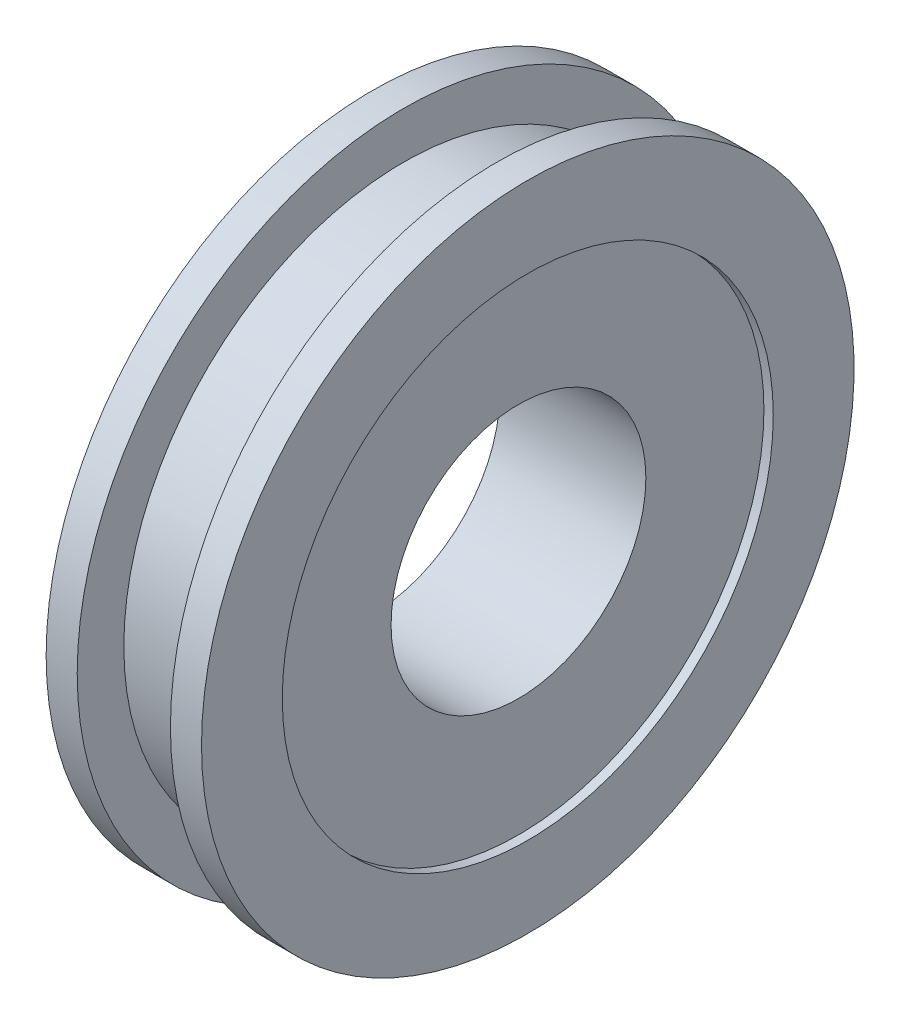
SolidWorks part; units mm, degrees
ref_plane "Front Plane" through (0, 0, 0) normal (0, 0, 1) x (1, 0, 0)
ref_plane "Top Plane" through (0, 0, 0) normal (0, 1, 0) x (1, 0, 0)
ref_plane "Right Plane" through (0, 0, 0) normal (1, 0, 0) x (0, 0, -1)
sketch "Sketch1" plane through (0, 0, 0) normal (0, 0, 1) x (1, 0, 0)
  line L0 (0, 0) -> (5.1881, 0) construction
  line L2 (-5.5, -0.875) -> (-5.5, 10.5) construction
  line L3 (-5.5, 10.5) -> (-0.5, 10.5)
  line L4 (-0.5, 4.1) -> (-0.5, 10.5)
  line L5 (-5.5, 10.5) -> (-5.5, 4.1)
  line L8 (-5.5, 4.1) -> (-0.5, 4.1)
  dimension "D1" = 10.5
  dimension "D2" = 5
  dimension "D5" = 4.1
revolve "Revolve1" add sketch "Sketch1" angle 360 about L0
sketch "Sketch2" plane through (0, 0, 0) normal (0, 0, 1) x (1, 0, 0)
  line L6 (0, 0) -> (5.4705, 0) construction
  line L9 (-0.5, 3.3693) -> (-0.5, 10.5) construction
  line L10 (-0.5, 10.5) -> (-1.5, 10.5) construction
  line L11 (-1.5, 10.5) -> (-1.5, 9) construction
  line L12 (-1.5, 9) -> (-5.5, 9) construction
  line L13 (-5.5, 9) -> (-5.5, 3.3693) construction
  line L14 (-0.5, 10.5) -> (-5.5, 10.5) construction
  line L15 (-0.5, -10.5) -> (-0.5, 10.5) construction
  line L16 (-5.5, 10.5) -> (-5.5, -10.5) construction
  line L17 (-1.5, 9) -> (-1.5, 10.5)
  line L18 (-1.5, 10.5) -> (-4.5, 10.5)
  line L20 (-4.5, 10.5) -> (-4.5, 9)
  line L21 (-4.5, 9) -> (-1.5, 9)
  line L22 (-4.5, 10.5) -> (-5.5, 10.5) construction
  line L23 (-1.5, 10.5) -> (-0.5, 10.5) construction
  dimension "D1" = 9
  dimension "D2" = 3
  dimension "D3" = 1
  dimension "D5" = 1.5
revolve "Cut-Revolve1" cut sketch "Sketch2" angle 360 about L6
sketch "Sketch3" plane through (0, 0, 0) normal (1, 0, 0) x (0, 0, -1)
  circle A0 centre (0, 0) radius 7.9
  dimension "D1" = 15.8
extrude "Cut-Extrude1" cut sketch "Sketch3" against normal blind 0.8
sketch "Sketch5" plane through (-5.5, 0, 0) normal (-1, 0, 0) x (0, 0, 1)
  text T0 "<b>18</b>"
extrude "Cut-Extrude2" cut sketch "Sketch5" against normal blind 1
